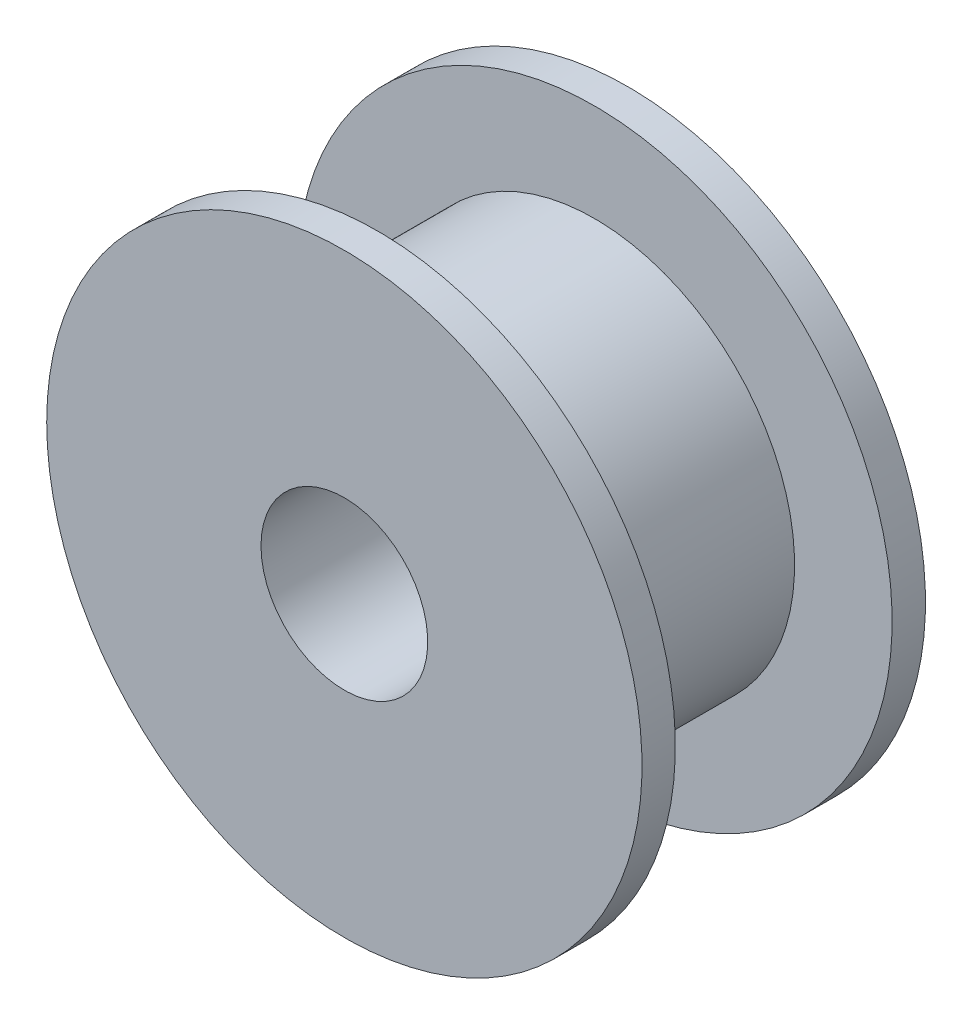
SolidWorks part; units mm, degrees
ref_plane "Front Plane" through (0, 0, 0) normal (0, 0, 1) x (1, 0, 0)
ref_plane "Top Plane" through (0, 0, 0) normal (0, 1, 0) x (1, 0, 0)
ref_plane "Right Plane" through (0, 0, 0) normal (1, 0, 0) x (0, 0, -1)
sketch "Sketch6" plane through (0, 0, 0) normal (0, 0, 1) x (1, 0, 0)
  circle A0 centre (0, 0) radius 6
  dimension "D1" = 12
extrude "Boss-Extrude1" add sketch "Sketch6" along normal blind 3.25
sketch "Sketch8" plane through (0, 0, 0) normal (0, 0, -1) x (-1, 0, 0)
  circle A0 centre (0, 0) radius 8.925
  dimension "D1" = 17.85
extrude "Boss-Extrude2" add sketch "Sketch8" along normal blind 1
sketch "Sketch9" plane through (0, 0, -1) normal (0, 0, -1) x (-1, 0, 0)
  circle A0 centre (0, 0) radius 2.5
  dimension "D1" = 5
extrude "Cut-Extrude1" cut sketch "Sketch9" against normal through all
mirror "Mirror2" about plane through (0, 0, 3.25) normal (0, 0, 1) of "Boss-Extrude2", "Boss-Extrude1", "Cut-Extrude1"
